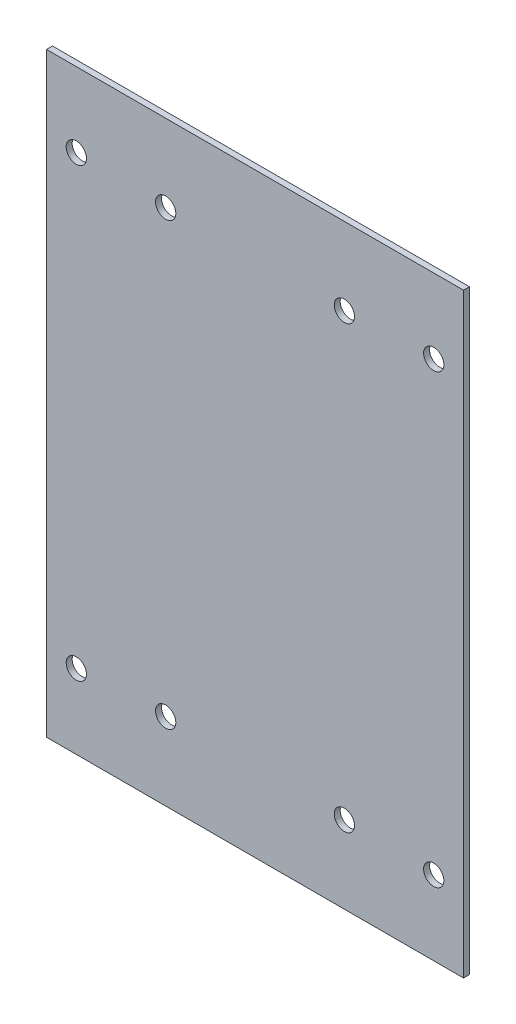
SolidWorks part; units mm, degrees
ref_plane "Front Plane" through (0, 0, 0) normal (0, 0, 1) x (1, 0, 0)
ref_plane "Top Plane" through (0, 0, 0) normal (0, 1, 0) x (1, 0, 0)
ref_plane "Right Plane" through (0, 0, 0) normal (1, 0, 0) x (0, 0, -1)
sketch "Sketch1" plane through (0, 0, 0) normal (0, 0, 1) x (1, 0, 0)
  line L1 (-35, -50) -> (35, -50)
  line L2 (-35, -50) -> (-35, 50)
  line L3 (-35, 50) -> (35, 50)
  line L4 (35, -50) -> (35, 50)
  line L5 (-35, -50) -> (35, 50) construction
  line L6 (-35, 50) -> (35, -50) construction
  point P0 (0, 0)
extrude "Boss-Extrude1" add sketch "Sketch1" against normal blind 1
sketch "Sketch2" plane through (0, 0, 0) normal (0, 0, 1) x (1, 0, 0)
  circle A0 centre (-30, -37.5) radius 1.7
  circle A1 centre (-30, 37.5) radius 1.7
  circle A2 centre (30, -37.5) radius 1.7
  circle A3 centre (30, 37.5) radius 1.7
extrude "Cut-Extrude1" cut sketch "Sketch2" along normal through all and the other way through all
sketch "Sketch3" plane through (0, 0, 0) normal (0, 0, 1) x (1, 0, 0)
  circle A0 centre (-15, -37) radius 1.7
  circle A1 centre (-15, 37) radius 1.7
  circle A2 centre (15, -37) radius 1.7
  circle A3 centre (15, 37) radius 1.7
extrude "Lo_M3_bat_driver" cut sketch "Sketch3" along normal through all and the other way through all
